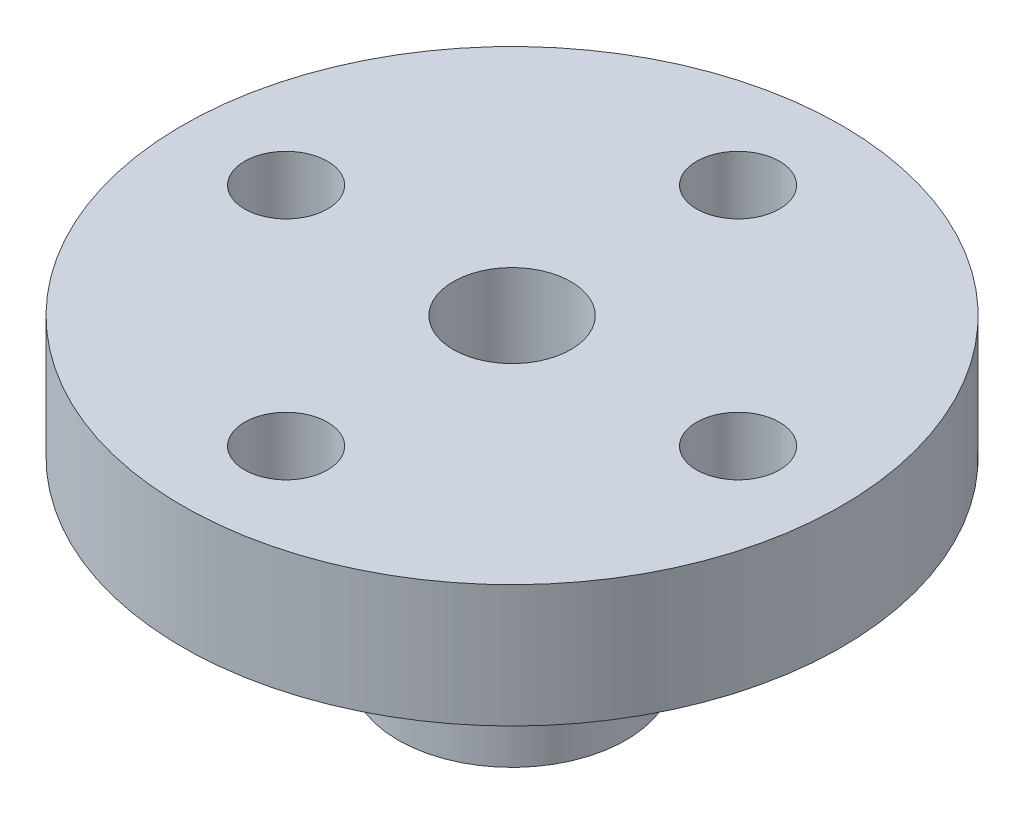
SolidWorks part; units mm, degrees
ref_plane "Front Plane" through (0, 0, 0) normal (0, 0, 1) x (1, 0, 0)
ref_plane "Top Plane" through (0, 0, 0) normal (0, 1, 0) x (1, 0, 0)
ref_plane "Right Plane" through (0, 0, 0) normal (1, 0, 0) x (0, 0, -1)
sketch "Sketch1" plane through (0, 0, 0) normal (0, 1, 0) x (1, 0, 0)
  circle A0 centre (0, 0) radius 3.05
  circle A1 centre (0, 0) radius 6.05
  dimension "D1" = 6.1
  dimension "D2" = 3
extrude "Boss-Extrude1" add sketch "Sketch1" along normal blind 10
sketch "Sketch2" plane through (0, 10, 0) normal (0, 1, 0) x (1, 0, 0)
  circle A0 centre (0, 0) radius 17.5
  dimension "D1" = 35
extrude "Boss-Extrude2" add sketch "Sketch2" along normal blind 6.5
sketch "Sketch3" plane through (0, 10, 0) normal (0, -1, 0) x (1, 0, 0)
  circle A0 centre (12, 0) radius 2.2
  circle A1 centre (0, -12) radius 2.2
  circle A2 centre (-12, 0) radius 2.2
  circle A3 centre (0, 12) radius 2.2
  point P11 (0, 0)
  dimension "D1" = 4.4
  dimension "D3" = 12
  dimension "D2" = 4
extrude "Cut-Extrude1" cut sketch "Sketch3" against normal up to next
sketch "Sketch4" plane through (0, 0, 0) normal (1, 0, 0) x (0, 0, -1)
  circle A0 centre (0, 4.9164) radius 1.5
  dimension "D1" = 3
extrude "Cut-Extrude2" cut sketch "Sketch4" against normal through all both and the other way through all
sketch "Sketch6" plane through (0, 10, 0) normal (0, -1, 0) x (-1, 0, 0)
  circle A0 centre (0, 0) radius 3.125
  dimension "D1" = 6.25
extrude "Cut-Extrude3" cut sketch "Sketch6" against normal up to next and the other way up to next
